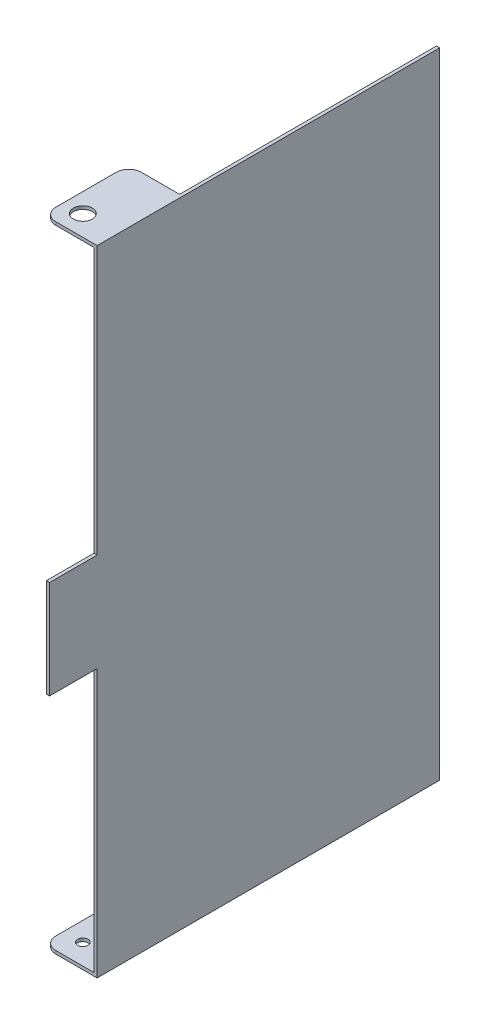
SolidWorks part; units mm, degrees
ref_plane "Front Plane" through (0, 0, 0) normal (1, 0, 0) x (0, 1, 0)
ref_plane "Top Plane" through (0, 0, 0) normal (0, 0, 1) x (0, 1, 0)
ref_plane "Right Plane" through (0, 0, 0) normal (0, 1, 0) x (-1, 0, 0)
sketch "Sketch1" plane through (0, 0, 0) normal (1, 0, 0) x (0, 1, 0)
  line L1 (-100, 54) -> (100, 54)
  line L2 (-100, 54) -> (-100, -54)
  line L3 (-100, -54) -> (100, -54)
  line L4 (100, 54) -> (100, -54)
  line L5 (-100, 54) -> (100, -54) construction
  line L6 (-100, -54) -> (100, 54) construction
  point P0 (0, 0)
  dimension "D1" = 200
  dimension "D2" = 108
extrude "Boss-Extrude1" add sketch "Sketch1" against normal blind 1
sketch "Sketch3" plane through (0, 100, 0) normal (0, 1, 0) x (-1, 0, 0)
  line L1 (1, 54) -> (17, 54)
  line L2 (1, 54) -> (1, 27)
  line L3 (1, 27) -> (17, 27)
  line L4 (17, 54) -> (17, 27)
  dimension "D1" = 27
  dimension "D2" = 16
extrude "Boss-Extrude2" add sketch "Sketch3" against normal blind 1
sketch "Sketch4" plane through (0, 100, 0) normal (0, 1, 0) x (-1, 0, 0)
  line L0 (1, 27) -> (17, 27) construction
  line L1 (17, 27) -> (17, 54) construction
  circle A0 centre (11, 47.5) radius 3
  dimension "D1" = 20.5
  dimension "D2" = 6
extrude "Cut-Extrude1" cut sketch "Sketch4" against normal up to next contours A0
fillet "Fillet2" radius 4 2 edges at (-17, 99.5, 27) (-17, 99.5, 54)
mirror "Mirror1" about plane through (0, 0, 0) normal (0, 1, 0) of "Boss-Extrude2"
sketch "Sketch6" plane through (0, -100, 0) normal (0, -1, 0) x (1, 0, 0)
  line L0 (-17, 27) -> (-17, 54) construction
  line L1 (-1, 27) -> (-17, 27) construction
  circle A0 centre (-11, 47.5) radius 1.65
  dimension "D1" = 6
  dimension "D2" = 20.5
extrude "Cut-Extrude2" cut sketch "Sketch6" against normal up to next
fillet "Fillet3" radius 4 2 edges at (-17, -99.5, 54) (-17, -99.5, 27)
sketch "Sketch7" plane through (0, 0, 54) normal (0, 0, 1) x (1, 0, 0)
  line L0 (-1, 99) -> (-1, -99) construction
  line L1 (-1, 15.5) -> (0, 15.5)
  line L2 (-1, 15.5) -> (-1, -15.5)
  line L3 (-1, -15.5) -> (0, -15.5)
  line L4 (0, 15.5) -> (0, -15.5)
  line L5 (0, 100) -> (0, -100) construction
  dimension "D1" = 31
  dimension "D2" = 15.5
extrude "Boss-Extrude3" add sketch "Sketch7" against normal mid plane 30
